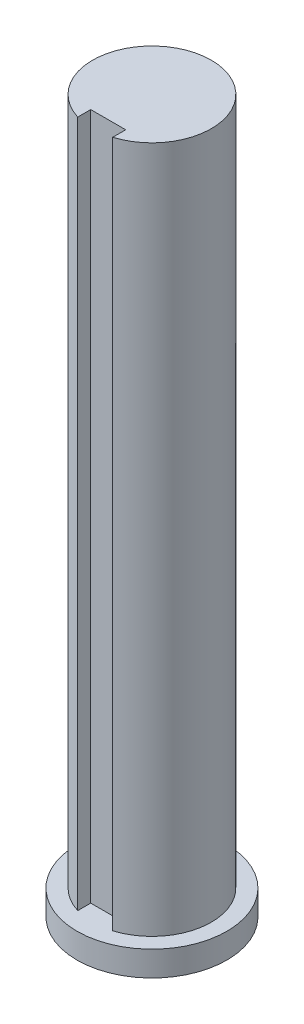
SolidWorks part; units mm, degrees
ref_plane "Front Plane" through (0, 0, 0) normal (0, 0, 1) x (1, 0, 0)
ref_plane "Top Plane" through (0, 0, 0) normal (0, 1, 0) x (1, 0, 0)
ref_plane "Right Plane" through (0, 0, 0) normal (1, 0, 0) x (0, 0, -1)
sketch "Sketch1" plane through (0, 0, 0) normal (0, 1, 0) x (1, 0, 0)
  circle A0 centre (0, 0) radius 7.62
  dimension "D1" = 15.24
extrude "Boss-Extrude1" add sketch "Sketch1" along normal blind 2.54
sketch "Sketch2" plane through (0, 2.54, 0) normal (0, 1, 0) x (-1, 0, 0)
  line L0 (0, 0) -> (0, 6.0325) construction
  line L2 (-1.778, 4.445) -> (1.778, 4.445)
  line L3 (-1.778, 4.445) -> (-1.778, 7.62)
  line L4 (-1.778, 7.62) -> (1.778, 7.62)
  line L5 (1.778, 4.445) -> (1.778, 7.62)
  line L6 (-1.778, 4.445) -> (1.778, 7.62) construction
  line L7 (-1.778, 7.62) -> (1.778, 4.445) construction
  circle A0 centre (0, 0) radius 6.0325
  dimension "D1" = 12.065
  dimension "D2" = 3.556
  dimension "D3" = 3.175
extrude "Boss-Extrude2" add sketch "Sketch2" along normal blind 69.85 contours L3 A0 L5 L2
